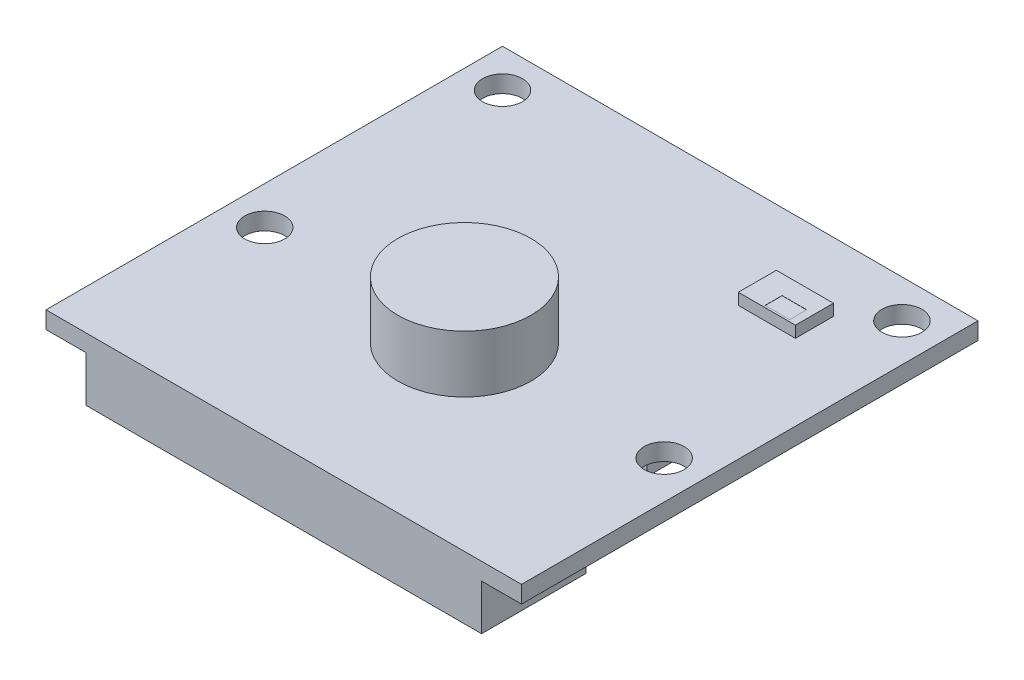
SolidWorks part; units mm, degrees
material "Epoxid, Ungefüllt"
ref_plane "Vorne" through (0, 0, 0) normal (0, 0, 1) x (1, 0, 0)
ref_plane "Oben" through (0, 0, 0) normal (0, 1, 0) x (1, 0, 0)
ref_plane "Rechts" through (0, 0, 0) normal (1, 0, 0) x (0, 0, -1)
sketch "Skizze1" plane through (0, 0, 0) normal (0, 1, 0) x (1, 0, 0)
  line L0 (0, 14.5) -> (0, -9.5) construction
  line L1 (-12.5, 14.5) -> (12.5, 14.5)
  line L2 (-12.5, 14.5) -> (-12.5, -9.5)
  line L3 (-12.5, -9.5) -> (12.5, -9.5)
  line L4 (12.5, 14.5) -> (12.5, -9.5)
  dimension "D1" = 24
  dimension "D2" = 25
  dimension "D3" = 9.5
extrude "PCB" add sketch "Skizze1" against normal blind 0.9
sketch "Skizze2" plane through (0, 0, 0) normal (0, 1, 0) x (1, 0, 0)
  line L0 (12.5, 14.5) -> (-12.5, 14.5) construction
  line L1 (12.5, -9.5) -> (12.5, 14.5) construction
  line L2 (0, 0) -> (0, 9.3158) construction
  circle A0 centre (10.5, 12.5) radius 1.05
  circle A1 centre (10.5, 0) radius 1.05
  circle A2 centre (-10.5, 0) radius 1.05
  circle A3 centre (-10.5, 12.5) radius 1.05
  dimension "D1" = 2.1
  dimension "D2" = 2
  dimension "D3" = 2
  dimension "D4" = 12.5
extrude "Mounting_Holes" cut sketch "Skizze2" against normal through all
sketch "Skizze3" plane through (0, -0.9, 0) normal (0, -1, 0) x (1, 0, 0)
  line L0 (0, 4) -> (0, 0) construction
  line L1 (-10.4, 9.5) -> (10.4, 9.5)
  line L2 (-10.4, 9.5) -> (-10.4, 4)
  line L3 (-10.4, 4) -> (10.4, 4)
  line L4 (10.4, 9.5) -> (10.4, 4)
  line L5 (-12.5, 9.5) -> (12.5, 9.5) construction
  dimension "D1" = 20.8
  dimension "D2" = 5.5
extrude "Connector_closed" add sketch "Skizze3" along normal blind 2.4
sketch "Skizze4" plane through (0, -0.9, 0) normal (0, -1, 0) x (1, 0, 0)
  line L0 (-12.5, -14.5) -> (-12.5, 9.5) construction
  line L1 (-9, -0.9) -> (8.7, -0.9)
  line L2 (-9, -0.9) -> (-9, -12.5)
  line L3 (-9, -12.5) -> (8.7, -12.5)
  line L4 (8.7, -0.9) -> (8.7, -12.5)
  line L5 (12.5, -14.5) -> (-12.5, -14.5) construction
  dimension "D1" = 17.7
  dimension "D2" = 3.5
  dimension "D3" = 2
  dimension "D4" = 13.6
extrude "Components_worst-case_Boundary-Box" add sketch "Skizze4" along normal blind 1.3
sketch "Skizze5" plane through (0, 0, 0) normal (1, 0, 0) x (0, 0, -1)
  line L0 (-9.5, -3.3) -> (-9.5, -0.9) construction
  line L1 (-9.5, 0) -> (14.5, 0) construction
  line L2 (-19.1541, -2.1) -> (0.1541, -2.1) construction
  line L3 (-158.9972, -1.9259) -> (-164.839, -3.2942)
  spline S0 degree 3 poles (-9.5, -2.1) (-29.5972, -2.1) (-48.1056, 0.935) (-88.623, -8.1953) (-134.4443, 3.8252) (-158.9972, -1.9259) knots 0 0 0 0 0.414692 0.514692 1 1 1 1
  dimension "D1" = 2.1
  dimension "D2" = 6
sketch "Skizze6" plane through (0, 0, 9.5) normal (0, 0, 1) x (1, 0, 0)
  line L1 (-8, -2.1) -> (8, -2.1)
  line L2 (-8, -2.1) -> (-8, -2.5)
  line L3 (-8, -2.5) -> (8, -2.5)
  line L4 (8, -2.1) -> (8, -2.5)
  dimension "D1" = 16
  dimension "D2" = 0.4
sweep "Cable_156mm_free_Length" [suppressed] add profiles "Skizze6" path "Skizze5"
sketch "Skizze7" plane through (0, 0, 0) normal (0, 1, 0) x (1, 0, 0)
  line L0 (12.5, 14.5) -> (-12.5, 14.5) construction
  line L1 (5.5, 10.9) -> (8.5, 10.9)
  line L2 (5.5, 10.9) -> (5.5, 8.9)
  line L3 (5.5, 8.9) -> (8.5, 8.9)
  line L4 (8.5, 10.9) -> (8.5, 8.9)
  line L5 (12.5, -9.5) -> (12.5, 14.5) construction
  dimension "D1" = 5.6
  dimension "D2" = 3.6
  dimension "D3" = 4
  dimension "D4" = 7
extrude "Components_worst-case_Boundary-Box2" add sketch "Skizze7" along normal blind 0.6
sketch "Skizze8" plane through (0, 0.6, 0) normal (0, 1, 0) x (1, 0, 0)
  line L0 (12.5, -9.5) -> (12.5, 14.5) construction
  line L1 (8.1, 9) -> (6.8, 9)
  line L2 (8.1, 9) -> (8.1, 9.9)
  line L3 (8.1, 9.9) -> (6.8, 9.9)
  line L4 (6.8, 9) -> (6.8, 9.9)
  line L5 (12.5, 14.5) -> (-12.5, 14.5) construction
  dimension "D1" = 1.3
  dimension "D2" = 0.9
  dimension "D3" = 4.4
  dimension "D4" = 4.6
extrude "Status_LED" cut sketch "Skizze8" against normal blind 0.01
sketch "Esboço1" plane through (0, 0, 0) normal (0, 1, 0) x (1, 0, 0)
  circle A0 centre (0, 0) radius 3.5
extrude "Ressalto-extrusão2" add sketch "Esboço1" along normal blind 3
